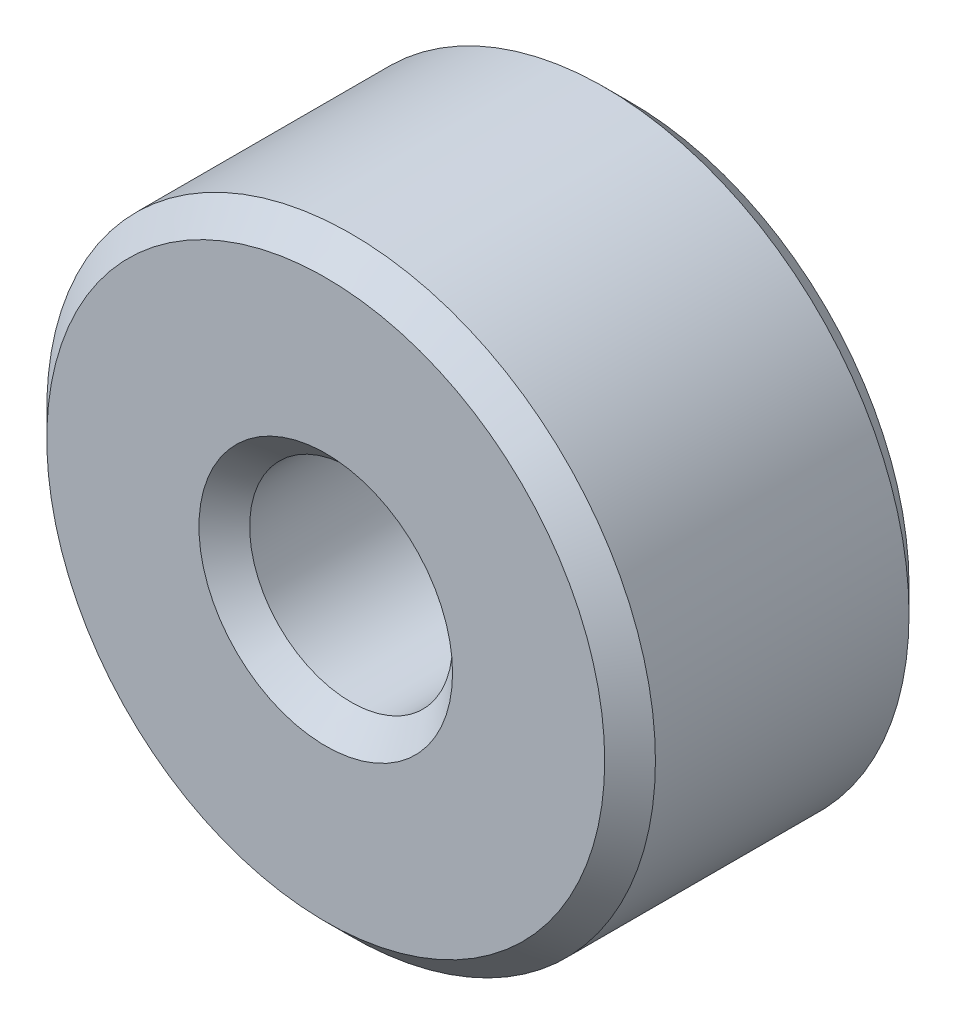
SolidWorks part; units mm, degrees
ref_plane "Front Plane" through (0, 0, 0) normal (0, 0, 1) x (1, 0, 0)
ref_plane "Top Plane" through (0, 0, 0) normal (0, 1, 0) x (1, 0, 0)
ref_plane "Right Plane" through (0, 0, 0) normal (1, 0, 0) x (0, 0, -1)
sketch "Sketch1" plane through (0, 0, 0) normal (0, 0, 1) x (1, 0, 0)
  circle A0 centre (0, 0) radius 1
  dimension "D1" = 2
extrude "Extrude-Thin1" add sketch "Sketch1" along normal blind 3 thin
chamfer "Chamfer1" distance 0.25 angle 45 4 edges at (1, 0, 0) (3, 0, 0) (1, 0, 3) (3, 0, 3)
scale "Scale1" scale about origin uniform scaling yes scale factor 0.445
